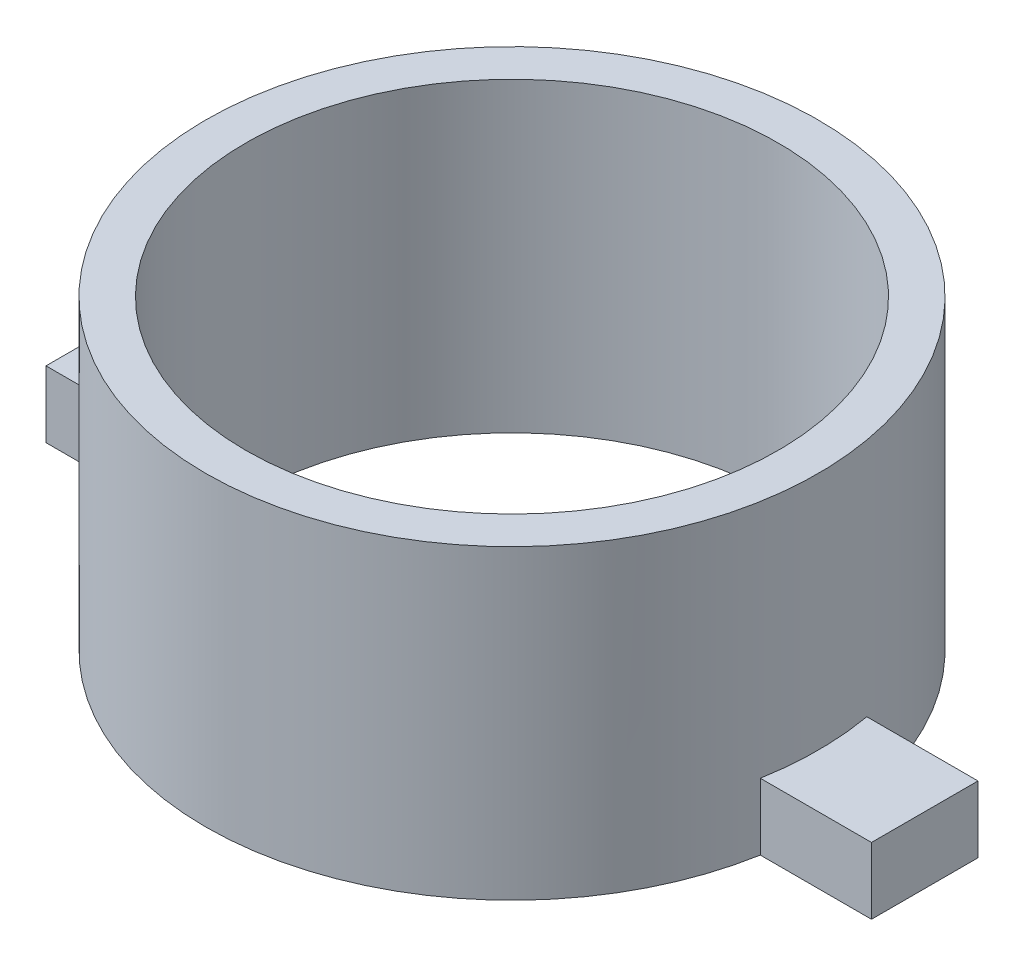
SolidWorks part; units mm, degrees
ref_plane "前视基准面" through (0, 0, 0) normal (0, 0, 1) x (1, 0, 0)
ref_plane "上视基准面" through (0, 0, 0) normal (0, 1, 0) x (1, 0, 0)
ref_plane "右视基准面" through (0, 0, 0) normal (1, 0, 0) x (0, 0, -1)
sketch "草图1" plane through (0, 0, 0) normal (0, 1, 0) x (1, 0, 0)
  circle A0 centre (0, 0) radius 20
  circle A1 centre (0, 0) radius 23
  dimension "D1" = 40
  dimension "D2" = 46
extrude "凸台-拉伸1" add sketch "草图1" along normal blind 23
sketch "草图3" plane through (0, 0, 0) normal (0, 0, 1) x (1, 0, 0)
  line L0 (-23, 23) -> (-23, 0) construction
  line L1 (-22, 0) -> (-31, 0)
  line L2 (-22, 0) -> (-22, 5)
  line L3 (-22, 5) -> (-31, 5)
  line L4 (-31, 0) -> (-31, 5)
  line L5 (25.3, 0) -> (-25.3, 0) construction
  dimension "D1" = 5
  dimension "D2" = 9
  dimension "D3" = 1
extrude "凸台-拉伸2" add sketch "草图3" along normal mid plane 8
mirror "镜向1" about plane through (0, 0, 0) normal (1, 0, 0) of "凸台-拉伸2"
